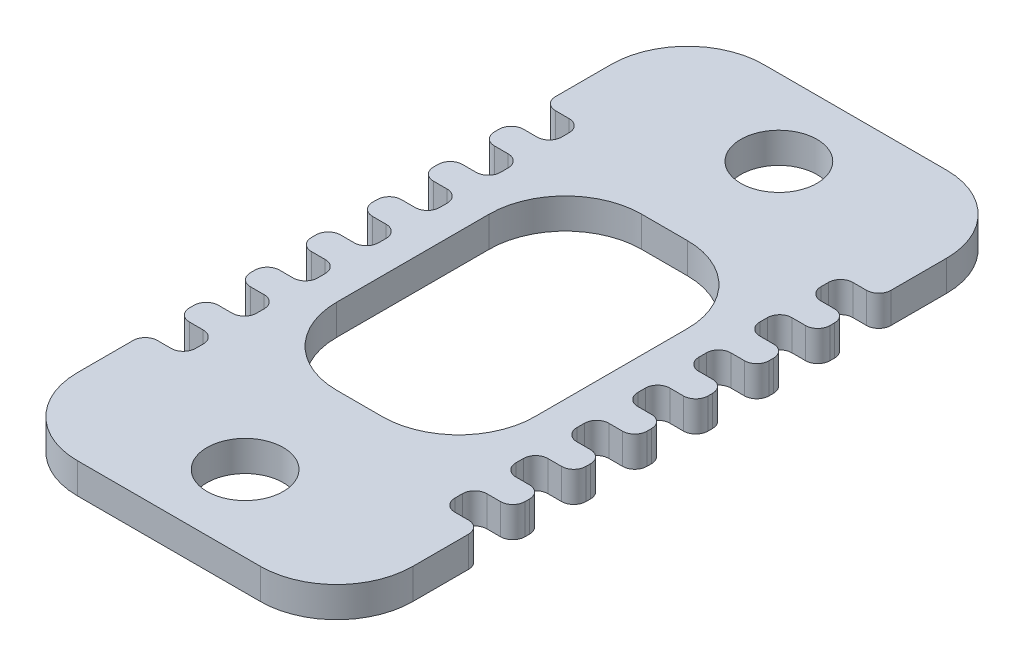
SolidWorks part; units mm, degrees
material "S355JR"
ref_plane "Front Plane" through (0, 0, 0) normal (0, 0, 1) x (1, 0, 0)
ref_plane "Top Plane" through (0, 0, 0) normal (0, 1, 0) x (1, 0, 0)
ref_plane "Right Plane" through (0, 0, 0) normal (1, 0, 0) x (0, 0, -1)
sketch "Sketch1" plane through (0, 0, 0) normal (0, 1, 0) x (1, 0, 0)
  line L0 (0, 17.5) -> (0, -17.5) construction
  line L1 (-6, -22.5) -> (6, -22.5)
  line L2 (-11, -17.5) -> (-11, 17.5)
  line L3 (-6, 22.5) -> (6, 22.5)
  line L4 (11, -17.5) -> (11, 17.5)
  line L5 (-11, -22.5) -> (11, 22.5) construction
  line L6 (-11, 22.5) -> (11, -22.5) construction
  arc A0 (-6, -22.5) -> (-11, -17.5) centre (-6, -17.5) cw
  arc A1 (6, -22.5) -> (11, -17.5) centre (6, -17.5) ccw
  arc A2 (6, 22.5) -> (11, 17.5) centre (6, 17.5) cw
  arc A3 (-11, 17.5) -> (-6, 22.5) centre (-6, 17.5) cw
  circle A4 centre (0, 17.5) radius 2.5
  circle A5 centre (0, -17.5) radius 2.5
  point P0 (0, 0)
  dimension "D3" = 5
  dimension "D5" = 5
  dimension "D1" = 45
  dimension "D2" = 22
  dimension "D4" = 5
extrude "Boss-Extrude1" add sketch "Sketch1" along normal blind 2
sketch "Sketch2" plane through (0, 2, 0) normal (0, 1, 0) x (1, 0, 0)
  line L5 (-11, -1.85) -> (-11, 1.85)
  line L6 (-11, 17.5) -> (-11, -17.5) construction
  line L7 (-10.2, 1.05) -> (-9.3, 1.05)
  line L8 (-8.5, 0.25) -> (-8.5, -0.25)
  line L9 (-9.3, -1.05) -> (-10.2, -1.05)
  arc A0 (-11, 1.85) -> (-10.2, 1.05) centre (-10.2, 1.85) ccw
  arc A1 (-9.3, 1.05) -> (-8.5, 0.25) centre (-9.3, 0.25) cw
  arc A2 (-8.5, -0.25) -> (-9.3, -1.05) centre (-9.3, -0.25) cw
  arc A3 (-10.2, -1.05) -> (-11, -1.85) centre (-10.2, -1.85) ccw
  point P5 (-11, 0)
  point P8 (-4.5, 0.4858)
  point P16 (0, 0)
  point P19 (-4.5, 0.6937)
  point P20 (-4.5387, 0.158)
  point P21 (-4.5686, 0.3967)
  point P22 (0, 0)
  point P24 (-7.263, -2.6438)
  dimension "D1" = 0.8
  dimension "D2" = 0.5
  dimension "D3" = 2.5
extrude "Cut-Extrude1" cut sketch "Sketch2" against normal blind 2
pattern_linear "LPattern2" count 4 spacing 4 along (0, 0, 1) count 4 spacing 4 along (0, 0, -1) of "Cut-Extrude1"
mirror "Mirror2" about plane through (0, 0, 0) normal (1, 0, 0) of "LPattern2", "Cut-Extrude1"
sketch "Sketch4" plane through (0, 2, 0) normal (0, 1, 0) x (1, 0, 0)
  line L0 (-8.5, -0.25) -> (-8.5, 0.25) construction
  line L1 (-1.5, -10) -> (1.5, -10)
  line L2 (-6.5, -5) -> (-6.5, 5)
  line L3 (-1.5, 10) -> (1.5, 10)
  line L4 (6.5, -5) -> (6.5, 5)
  line L5 (-6.5, -10) -> (6.5, 10) construction
  line L6 (-6.5, 10) -> (6.5, -10) construction
  arc A0 (-1.5, -10) -> (-6.5, -5) centre (-1.5, -5) cw
  arc A1 (1.5, -10) -> (6.5, -5) centre (1.5, -5) ccw
  arc A2 (1.5, 10) -> (6.5, 5) centre (1.5, 5) cw
  arc A3 (-6.5, 5) -> (-1.5, 10) centre (-1.5, 5) cw
  point P0 (0, 0)
  dimension "D3" = 5
  dimension "D1" = 2
  dimension "D2" = 20
extrude "Cut-Extrude3" cut sketch "Sketch4" against normal blind 2
equation "\"Temp Cut In\"= \"Cut In\""
equation "\"Temp Cut Out\"= \"Cut Out\""
equation "\"Temp Total Cut\"= \"Temp Cut In\" + \"Temp Cut Out\""
